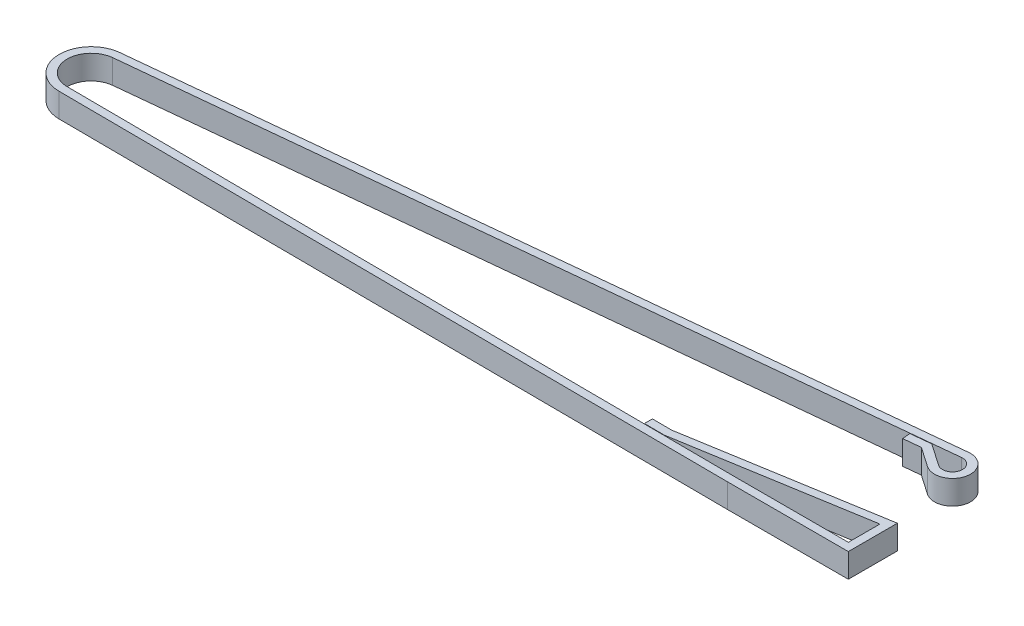
SolidWorks part; units mm, degrees
ref_plane "Front Plane" through (0, 0, 0) normal (0, 0, 1) x (1, 0, 0)
ref_plane "Top Plane" through (0, 0, 0) normal (0, 1, 0) x (1, 0, 0)
ref_plane "Right Plane" through (0, 0, 0) normal (1, 0, 0) x (0, 0, -1)
sketch "Sketch1" plane through (0, 49.4, 0) normal (0, 1, 0) x (1, 0, 0)
  line L0 (71.7752, 18) -> (99.9752, 18)
  line L1 (99.9752, 18) -> (99.9752, 25.9)
  line L2 (-96.1409, 19.0001) -> (71.7752, 18)
  line L3 (95.7478, 50.4872) -> (-96.7105, 30.9694)
  line L4 (99.9752, 25.9) -> (53.817, 18.207)
  line L5 (53.817, 18.207) -> (48.817, 18.2367)
  line L6 (99.9752, 25.9) -> (71.7752, 21.2) construction
  line L7 (94.5811, 45.9416) -> (89.1093, 49.7135)
  line L8 (89.1093, 49.7135) -> (84.1348, 49.209)
  circle A0 centre (-96.1051, 25) radius 6 construction
  arc A1 (95.7478, 50.4872) -> (94.5811, 45.9416) centre (96, 48) cw
  circle A6 centre (96, 48) radius 2.5 construction
  arc A7 (-96.7105, 30.9694) -> (-96.1409, 19.0001) centre (-96.1051, 25) ccw
  dimension "D1" = 5
  dimension "D2" = 0.1
  dimension "D3" = 5
  dimension "D4" = 0.1
extrude "Extrude-Thin1" add sketch "Sketch1" along normal mid plane 6 thin contours L2
